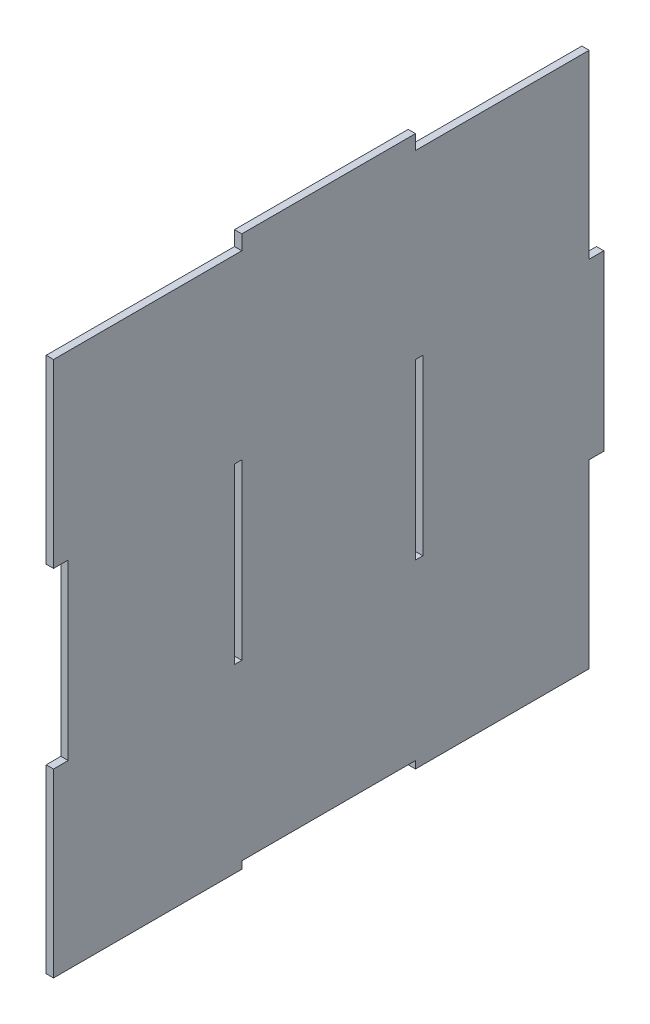
SolidWorks part; units mm, degrees
material "Delrin 2700 NC010, Low Viscosity Acetal Copolymer (SS)"
ref_plane "Front Plane" through (0, 0, 0) normal (0, 0, 1) x (1, 0, 0)
ref_plane "Top Plane" through (0, 0, 0) normal (0, 1, 0) x (1, 0, 0)
ref_plane "Right Plane" through (0, 0, 0) normal (1, 0, 0) x (0, 0, -1)
sketch "Sketch2" plane through (0, 0, 0) normal (1, 0, 0) x (0, 0, -1)
  line L0 (-113, 0) -> (-40.8417, 0)
  line L1 (-37.6667, 119.35) -> (-37.6667, 113)
  line L2 (-37.6667, 0) -> (37.6667, 0)
  line L3 (-37.6667, 119.35) -> (37.6667, 119.35)
  line L4 (119.35, 37.6667) -> (119.35, -37.6667)
  line L5 (-113, 37.6667) -> (-119.35, 37.6667)
  line L6 (-37.6667, 113) -> (37.6667, 113)
  line L7 (0, 119.35) -> (0, 113)
  line L8 (-113, 37.6667) -> (-113, -37.6667)
  line L9 (-113, 0) -> (-119.35, 0)
  line L10 (-37.6667, 116.175) -> (-116.175, 116.175)
  line L11 (-116.175, 116.175) -> (-116.175, 37.6667)
  line L12 (-116.175, 37.6667) -> (-113, 37.6667)
  line L13 (-113, 37.6667) -> (-113, -37.6667)
  line L14 (-40.8417, -37.6667) -> (-40.8417, 37.6667)
  line L15 (-40.8417, 37.6667) -> (-37.6667, 37.6667)
  line L16 (-37.6667, 37.6667) -> (-37.6667, -37.6667)
  line L17 (-119.35, 37.6667) -> (-119.35, -37.6667)
  line L18 (37.6667, 37.6667) -> (37.6667, -37.6667)
  line L19 (40.8417, 37.6667) -> (37.6667, 37.6667)
  line L20 (40.8417, -37.6667) -> (40.8417, 37.6667)
  line L21 (113, 37.6667) -> (113, -37.6667)
  line L22 (116.175, 37.6667) -> (113, 37.6667)
  line L23 (116.175, 116.175) -> (116.175, 37.6667)
  line L24 (0, 119.35) -> (0, -119.35)
  line L25 (37.6667, 116.175) -> (116.175, 116.175)
  line L26 (113, 0) -> (119.35, 0)
  line L27 (113, 37.6667) -> (113, -37.6667)
  line L28 (113, 37.6667) -> (119.35, 37.6667)
  line L29 (37.6667, 119.35) -> (37.6667, 113)
  line L30 (113, 0) -> (40.8417, 0)
  line L31 (37.6667, -119.35) -> (37.6667, -113)
  line L32 (113, -37.6667) -> (119.35, -37.6667)
  line L33 (37.6667, -116.175) -> (116.175, -116.175)
  line L34 (116.175, -116.175) -> (116.175, -37.6667)
  line L35 (116.175, -37.6667) -> (113, -37.6667)
  line L36 (40.8417, -37.6667) -> (37.6667, -37.6667)
  line L37 (-40.8417, -37.6667) -> (-37.6667, -37.6667)
  line L38 (-116.175, -37.6667) -> (-113, -37.6667)
  line L39 (-116.175, -116.175) -> (-116.175, -37.6667)
  line L40 (-37.6667, -116.175) -> (-116.175, -116.175)
  line L41 (0, -119.35) -> (0, -113)
  line L42 (-37.6667, -113) -> (37.6667, -113)
  line L43 (-113, -37.6667) -> (-119.35, -37.6667)
  line L44 (-37.6667, -119.35) -> (37.6667, -119.35)
  line L45 (-37.6667, -119.35) -> (-37.6667, -113)
  point P35 (0, 0)
  point P36 (0, 0)
  dimension "D1" = 3.175
  dimension "D2" = 37.6667
  dimension "D3" = 3.175
  dimension "D4" = 3.175
  dimension "D5" = 75.3333
  dimension "D6" = 75.3333
  dimension "D7" = 113
  dimension "D8" = 37.6667
  dimension "D9" = 113
  dimension "D10" = 3.175
  dimension "D11" = 3.175
  dimension "D13" = 0
  dimension "D14" = 0
extrude "Boss-Extrude1" add sketch "Sketch2" along normal blind 3.175 contours L24 L6 L1 L10 L11 L5 L8 L0 L14 L15 L16 L2 | L29 L3 L7 L6 | L30 L21 L22 L23 L25 L29 L6 L24 L2 L18 L19 L20 | L28 L22 L21 L26 L4 | L21 L32 L4 L26 | L24 L42 L31 L33 L34 L32 L21 L30 L20 L36 L18 L2 | L40 L45 L42 L24 L2 L16 L37 L14 L0 L8 L38 L39
sketch "Sketch3" plane through (3.175, 0, 0) normal (1, 0, 0) x (0, 0, -1)
  line L0 (-37.6667, -116.175) -> (-116.175, -116.175) construction
  line L1 (-116.175, 116.175) -> (-119.35, 116.175)
  line L2 (-116.175, 116.175) -> (-116.175, -116.175)
  line L3 (-116.175, -116.175) -> (-119.35, -116.175)
  line L4 (-119.35, 116.175) -> (-119.35, -116.175)
  line L5 (-116.175, -37.6667) -> (-113, -37.6667) construction
  line L6 (-113, 37.6667) -> (-119.35, 37.6667)
  line L7 (-113, 37.6667) -> (-113, -37.6667)
  line L8 (-113, -37.6667) -> (-119.35, -37.6667)
  line L9 (-119.35, 37.6667) -> (-119.35, -37.6667)
  line L10 (-37.6667, 119.35) -> (37.6667, 119.35) construction
  line L11 (37.6667, 116.175) -> (-37.6667, 116.175)
  line L12 (37.6667, 116.175) -> (37.6667, 122.525)
  line L13 (37.6667, 122.525) -> (-37.6667, 122.525)
  line L14 (-37.6667, 116.175) -> (-37.6667, 122.525)
  line L15 (-37.6667, 119.35) -> (-37.6667, 116.175) construction
  line M5 (37.6667, 119.35) -> (-37.6667, 119.35)
  line M8 (-116.175, 116.175) -> (-116.175, 37.6667)
  line M12 (-116.175, -37.6667) -> (-116.175, -116.175)
  dimension "D1" = 3.175
  dimension "D2" = 0
  dimension "D3" = 0
  dimension "D4" = 3.175
  dimension "D5" = 0
extrude "Boss-Extrude2" add sketch "Sketch3" against normal blind 3.175 contours L6 L1 L4 M8 | L8 L4 L3 M12 | L14 L12 L13 M5
sketch "Sketch4" plane through (3.175, 0, 0) normal (1, 0, 0) x (0, 0, -1)
  line L0 (37.6667, 116.175) -> (116.175, 116.175) construction
  line L1 (119.35, 37.6667) -> (113, 37.6667)
  line L2 (119.35, 37.6667) -> (119.35, 116.175)
  line L3 (119.35, 116.175) -> (113, 116.175)
  line L4 (113, 37.6667) -> (113, 116.175)
  line L5 (37.6667, -116.175) -> (116.175, -116.175) construction
  line L6 (113, 37.6667) -> (119.35, 37.6667)
  line L7 (113, 37.6667) -> (113, -37.6667)
  line L8 (113, -37.6667) -> (119.35, -37.6667)
  line L9 (119.35, 37.6667) -> (119.35, -37.6667)
  line L10 (119.35, -37.6667) -> (113, -37.6667)
  line L11 (119.35, -37.6667) -> (119.35, -116.175)
  line L12 (119.35, -116.175) -> (113, -116.175)
  line L13 (113, -37.6667) -> (113, -116.175)
  line L14 (116.175, 116.175) -> (116.175, 37.6667) construction
  line L16 (116.175, 116.175) -> (113, 116.175)
  line L17 (116.175, 116.175) -> (116.175, -116.175)
  line L18 (116.175, -116.175) -> (113, -116.175)
  line L19 (113, 116.175) -> (113, -116.175)
  line M13 (37.6667, -116.175) -> (116.175, -116.175)
  line M14 (116.175, -116.175) -> (116.175, -37.6667)
  line M18 (116.175, 37.6667) -> (116.175, 116.175)
  line M19 (116.175, 116.175) -> (37.6667, 116.175)
  dimension "D1" = 3.175
extrude "Cut-Extrude1" cut sketch "Sketch4" against normal blind 3.175 contours L4 L1 M18 M19 | L8 L13 M13 M14
equation "\"D8@Sketch2\"=\"D2@Sketch2\""
equation "\"D11@Sketch2\"=\"D3@Sketch2\""
equation "\"D4@Sketch2\"=\"D3@Sketch2\""
equation "\"D10@Sketch2\"=\"D3@Sketch2\""
equation "\"Resolution Projector X\"= 1920"
equation "\"Resolution Projector Y\"= 1080"
equation "\"Resolution Build\"= 0.1"
equation "\"Size Build Volume X\"= \"Resolution Projector X\" * \"Resolution Build\""
equation "\"Size Build Volume Y\"= 2 * \"Resolution Projector Y\" * \"Resolution Build\""
equation "\"Size Build Volume Z\"= \"Size Build Volume Y\""
equation "\"Size Enclosure Internal X\"= 350mm"
equation "\"Size Enclosure Internal Y\"= \"Size Enclosure Internal X\""
equation "\"Size Enclosure Internal Z\"= \"Size Enclosure Internal X\""
equation "\"Size Enclosure External Z\"= 1000mm"
equation "\"Clearance Vat\"= 10mm'd_ clearance vat data"
equation "\"Size Vat X\"= \"Size Build Volume X\" + \"Clearance Vat\"'f_ size vat data"
equation "\"Size Vat Y\"= \"Size Build Volume Y\" + \"Clearance Vat\"'f_ size vat data"
equation "\"Size Vat Z\"= \"Size Build Volume Z\" + \"Clearance Vat\"'f_ size vat data"
equation "\"Thickness Vat\"= 3.175mm'g_ thickness vat data"
equation "\"width rib\"= 2 * \"Thickness Vat\"'g_ thickness of the Rib"
equation "\"width Lip on rib\"= \"Thickness Vat\" * 2'g_ thickness of the lip connected to the tab"
equation "\"height Lip on rib\"= \"width Lip on rib\"'g_ height of lip on rib structure"
equation "\"height adjustment\"= \"Thickness Vat\" * 2'g_ height adjustment for lip.  This flushes the top part of the tab to top of the walls"
equation "\"goofy tab x\"= \"Size Vat X\" * ( 1 / 3 ) - \"width rib\"'h_ goofy slot found on rib X"
equation "\"goofy tab y\"= \"Size Vat Y\" * ( 1 / 3 ) - \"width rib\"'h_ goofy slot found on rib Y"
equation "\"D9@Sketch2\"=\"Size Vat Y\"/2mm"
equation "\"D5@Sketch2\"=\"D6@Sketch2\""
equation "\"D1@Sketch2\"=\"D10@Sketch2\""
equation "\"D2@Sketch2\"=\"D7@Sketch2\"/3"
equation "\"D6@Sketch2\"=\"Size Vat Y\"/3"
equation "\"D3@Sketch2\"=\"Thickness Vat\""
equation "\"D7@Sketch2\"=\"Size Vat Z\"/2"
equation "\"D1@Boss-Extrude1\"=\"Thickness Vat\""
equation "\"D1@Sketch3\"=\"Thickness Vat\""
equation "\"D1@Boss-Extrude2\"=\"Thickness Vat\""
equation "\"D1@Sketch4\"=\"Thickness Vat\""
equation "\"D1@Cut-Extrude1\"=\"Thickness Vat\""
equation "\"D4@Sketch3\"=\"Thickness Vat\""
